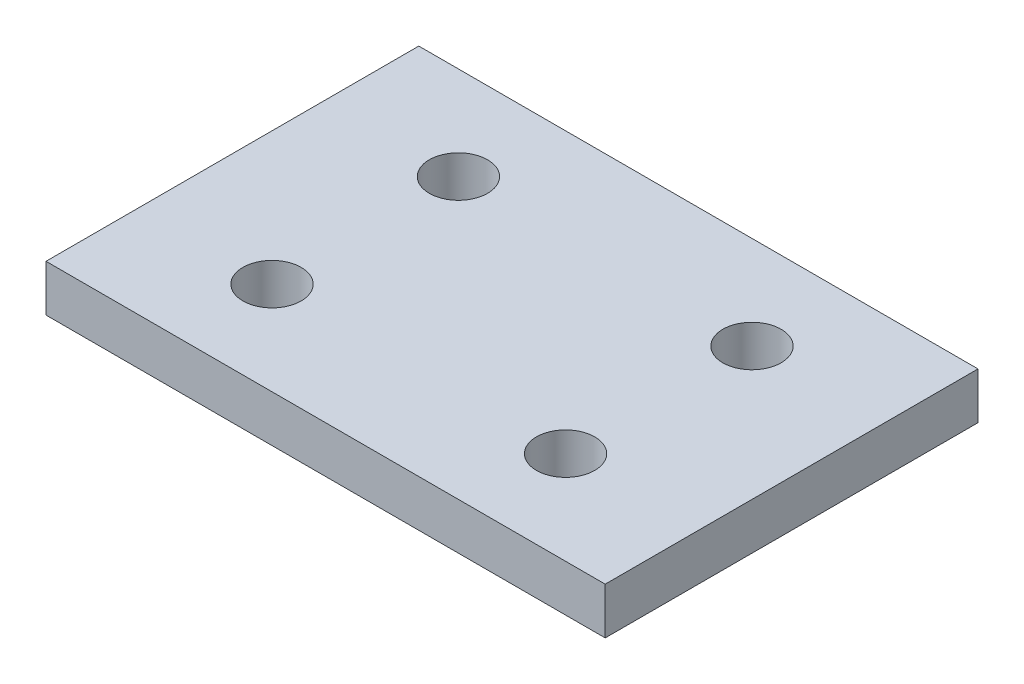
SolidWorks part; units mm, degrees
ref_plane "Front Plane" through (0, 0, 0) normal (0, 0, 1) x (1, 0, 0)
ref_plane "Top Plane" through (0, 0, 0) normal (0, 1, 0) x (1, 0, 0)
ref_plane "Right Plane" through (0, 0, 0) normal (1, 0, 0) x (0, 0, -1)
sketch "Sketch1" plane through (0, 0, 0) normal (0, 1, 0) x (1, 0, 0)
  line L1 (0, 0) -> (76.2, 0)
  line L2 (0, 0) -> (0, 50.8)
  line L3 (0, 50.8) -> (76.2, 50.8)
  line L4 (76.2, 0) -> (76.2, 50.8)
  dimension "D1" = 76.2
  dimension "D2" = 50.8
extrude "Boss-Extrude1" add sketch "Sketch1" along normal blind 6.35
sketch "Sketch3" plane through (0, 6.35, 0) normal (0, 1, 0) x (1, 0, 0)
  line L0 (18.1, 50.8) -> (18.1, 0) construction
  line L1 (76.2, 50.8) -> (0, 50.8) construction
  line L2 (0, 0) -> (76.2, 0) construction
  line L3 (58.1, 50.8) -> (58.1, 0) construction
  line L4 (18.1, 25.4) -> (58.1, 25.4) construction
  circle A0 centre (18.1, 38.1) radius 3.9688
  circle A1 centre (18.1, 12.7) radius 3.9688
  circle A2 centre (58.1, 38.1) radius 3.9687
  circle A3 centre (58.1, 12.7) radius 3.9687
  point P18 (38.1, 25.4)
  point P19 (38.1, 50.8)
  dimension "D5" = 7.9375
  dimension "D1" = 40
  dimension "D3" = 25.4
  dimension "D4" = 12.7
extrude "Cut-Extrude1" cut sketch "Sketch3" against normal through all
